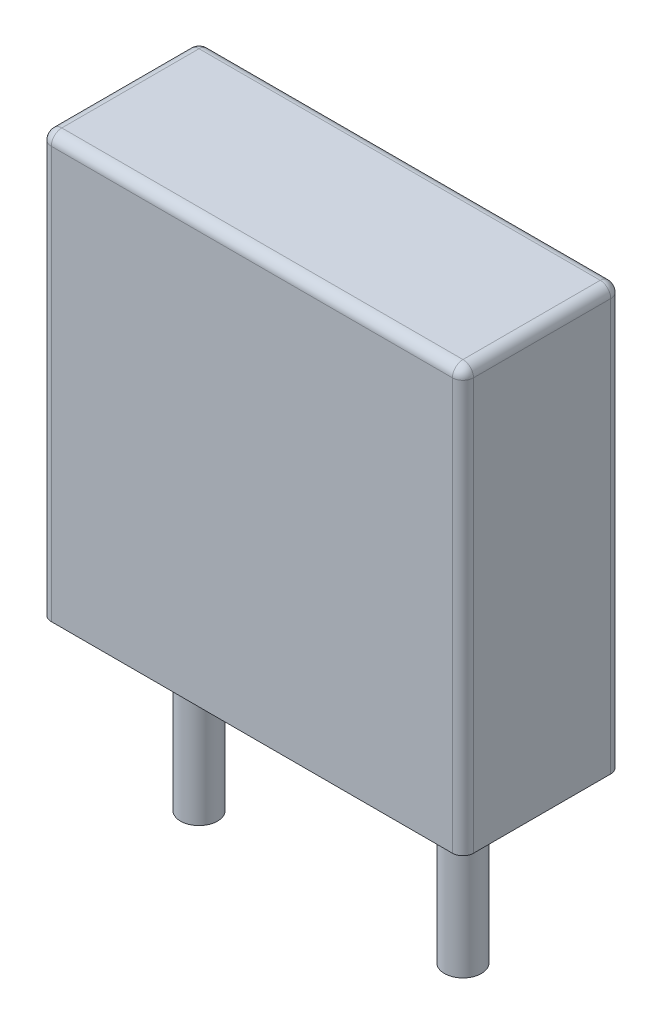
SolidWorks part; units mm, degrees
ref_plane "Спереди" through (0, 0, 0) normal (0, 0, 1) x (1, 0, 0)
ref_plane "Сверху" through (0, 0, 0) normal (0, 1, 0) x (1, 0, 0)
ref_plane "Справа" through (0, 0, 0) normal (1, 0, 0) x (0, 0, -1)
sketch "Эскиз1" plane through (0, 0, 0) normal (0, 1, 0) x (1, 0, 0)
  line L1 (-4, -1.5) -> (4, -1.5)
  line L2 (-4, -1.5) -> (-4, 1.5)
  line L3 (-4, 1.5) -> (4, 1.5)
  line L4 (4, -1.5) -> (4, 1.5)
  line L5 (-4, -1.5) -> (4, 1.5) construction
  line L6 (-4, 1.5) -> (4, -1.5) construction
  point P0 (0, 0)
  dimension "D1" = 3
  dimension "D2" = 8
extrude "Бобышка-Вытянуть1" add sketch "Эскиз1" along normal blind 8
sketch "Эскиз2" plane through (0, 0, 0) normal (0, -1, 0) x (1, 0, 0)
  line L0 (-2.5, 0) -> (2.5, 0) construction
  circle A0 centre (-2.5, 0) radius 0.35
  circle A1 centre (2.5, 0) radius 0.35
  point P4 (0, 0)
  dimension "D2" = 0.7
  dimension "D1" = 5
extrude "Бобышка-Вытянуть2" add sketch "Эскиз2" along normal blind 3.2
fillet "Скругление1" radius 0.2 8 edges at (0, 8, 1.5) (-4, 8, 0) (0, 8, -1.5) (4, 8, 0) (-4, 4, -1.5) (4, 4, -1.5) (4, 4, 1.5) (-4, 4, 1.5)
